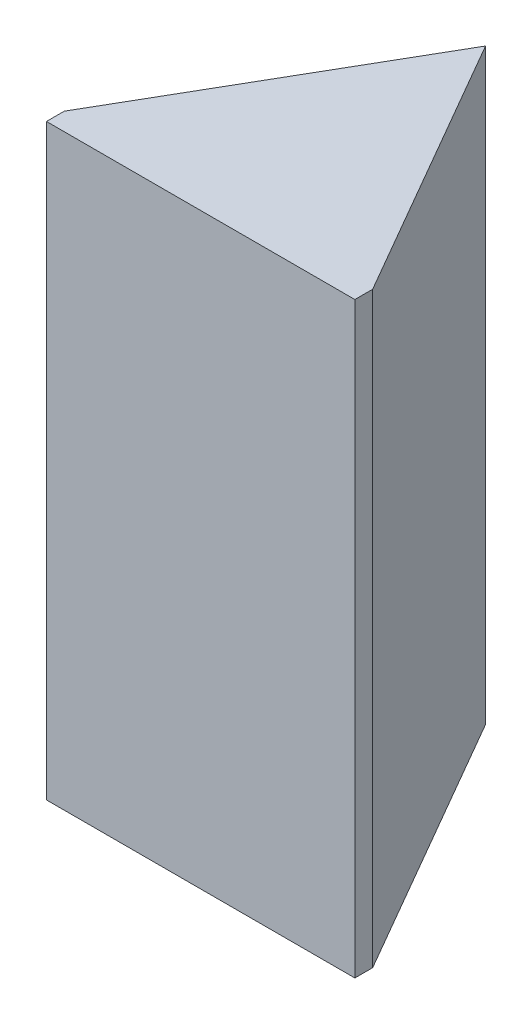
SolidWorks part; units mm, degrees
ref_plane "Front Plane" through (0, 0, 0) normal (0, 0, 1) x (1, 0, 0)
ref_plane "Top Plane" through (0, 0, 0) normal (0, 1, 0) x (1, 0, 0)
ref_plane "Right Plane" through (0, 0, 0) normal (1, 0, 0) x (0, 0, -1)
sketch "Sketch1" plane through (0, 0, 0) normal (0, 1, 0) x (1, 0, 0)
  line L0 (0, 0) -> (34.641, 0)
  line L1 (34.641, 0) -> (17.3205, 30)
  line L2 (17.3205, 30) -> (0, 0)
  line L5 (17.3205, 30) -> (17.3205, 10.4199) construction
  line L7 (0, 0) -> (34.641, 0)
  line L8 (0, 0) -> (0, -2)
  line L9 (0, -2) -> (34.641, -2)
  line L10 (34.641, 0) -> (34.641, -2)
  dimension "D1" = 30
  dimension "D2" = 60
  dimension "D3" = 30
  dimension "D4" = 34.641
  dimension "D5" = 2
extrude "Boss-Extrude1" add sketch "Sketch1" along normal mid plane 66
sketch "Sketch2" plane through (0, 0, 0) normal (0, 1, 0) x (1, 0, 0)
  circle A2 centre (0, 0) radius 5
  circle A3 centre (34.641, 0) radius 5
  dimension "D1" = 10
  dimension "D2" = 10
